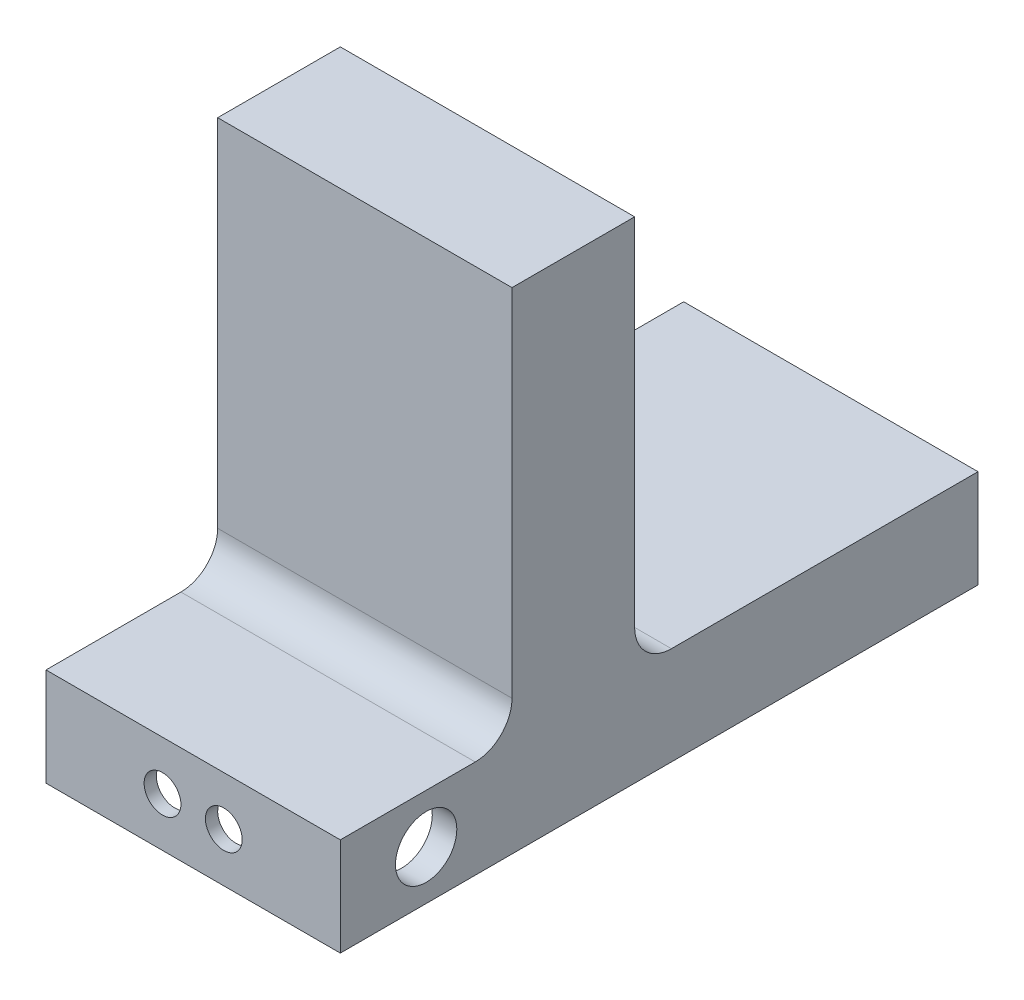
SolidWorks part; units mm, degrees
ref_plane "Plan de face" through (0, 0, 0) normal (0, 0, 1) x (1, 0, 0)
ref_plane "Plan de dessus" through (0, 0, 0) normal (0, 1, 0) x (1, 0, 0)
ref_plane "Plan de droite" through (0, 0, 0) normal (1, 0, 0) x (0, 0, -1)
sketch "Esquisse1" plane through (0, 0, 0) normal (0, 0, 1) x (1, 0, 0)
  line L0 (0, 40) -> (120, 40)
  line L1 (0, 0) -> (120, 0)
  line L2 (0, 0) -> (0, 200)
  line L3 (0, 200) -> (120, 200)
  line L4 (120, 0) -> (120, 200)
  dimension "D1" = 200
  dimension "D2" = 120
  dimension "D3" = 40
extrude "Boss.-Extru.2" add sketch "Esquisse1" along normal mid plane 50 contours L2 L1 L4 L3
sketch "Esquisse3" plane through (0, 0, 25) normal (0, 0, 1) x (1, 0, 0)
  line L0 (120, 0) -> (120, 200) construction
  line L1 (0, 0) -> (120, 0)
  line L2 (0, 0) -> (0, 40)
  line L3 (0, 40) -> (120, 40)
  line L4 (120, 0) -> (120, 40)
  dimension "D1" = 40
extrude "Boss.-Extru.3" add sketch "Esquisse3" along normal blind 70
fillet "Congé1" radius 15 1 edges at (60, 40, 25)
sketch "Esquisse4" plane through (0, 0, -25) normal (0, 0, -1) x (-1, 0, 0)
  line L0 (-120, 0) -> (-120, 200) construction
  line L1 (0, 0) -> (-120, 0)
  line L2 (0, 0) -> (0, 40)
  line L3 (0, 40) -> (-120, 40)
  line L4 (-120, 0) -> (-120, 40)
  dimension "D1" = 40
extrude "Boss.-Extru.4" add sketch "Esquisse4" along normal blind 140
fillet "Congé2" radius 15 1 edges at (60, 40, -25)
sketch "Esquisse5" plane through (0, 0, 95) normal (0, 0, 1) x (1, 0, 0)
  line L0 (0, 0) -> (120, 0) construction
  line L2 (120, 0) -> (120, 40) construction
  line L4 (35, 35) -> (85, 35)
  line L5 (35, 35) -> (35, 5)
  line L6 (35, 5) -> (85, 5)
  line L7 (85, 35) -> (85, 5)
  point P0 (60, 20)
  dimension "D1" = 20
  dimension "D2" = 60
  dimension "D3" = 25
  dimension "D4" = 50
  dimension "D5" = 30
  dimension "D6" = 15
extrude "Boss.-Extru.9" add sketch "Esquisse5" against normal blind 7.5
sketch "Esquisse7" plane through (0, 0, 0) normal (0, -1, 0) x (1, 0, 0)
  line L0 (0, 95) -> (0, -165) construction
  line L1 (10, 85) -> (110, 85)
  line L2 (10, 85) -> (10, 5)
  line L3 (10, 5) -> (110, 5)
  line L4 (110, 85) -> (110, 5)
  line L5 (0, 95) -> (120, 95) construction
  point P4 (60, 45)
  dimension "D1" = 60
  dimension "D2" = 50
  dimension "D3" = 100
  dimension "D4" = 50
  dimension "D5" = 40
  dimension "D6" = 80
extrude "Enlèv. mat.-Extru.1" cut sketch "Esquisse7" against normal blind 35
sketch "Esquisse8" plane through (0, 0, 95) normal (0, 0, 1) x (1, 0, 0)
  line L1 (120, 40) -> (0, 40) construction
  line L2 (0, 40) -> (0, 0) construction
  circle A0 centre (47.5, 20) radius 7.5
  circle A1 centre (72.5, 20) radius 7.5
  point P4 (77.7819, 21.8021)
  point P5 (45.6071, 21.8021)
  point P6 (73.2228, 21.8021)
  point P7 (0, 0)
  point P9 (40.2663, 34.8283)
  point P11 (0, 0)
  dimension "D2" = 15
  dimension "D3" = 15
  dimension "D1" = 25
  dimension "D4" = 20
  dimension "D5" = 47.5
extrude "Enlèv. mat.-Extru.7" cut sketch "Esquisse8" against normal up to next
sketch "Esquisse12" plane through (0, 0, 85) normal (0, 0, -1) x (-1, 0, 0)
  line L0 (-110, 35) -> (-110, 0) construction
  line L1 (-85, 35) -> (-35, 35)
  line L2 (-85, 35) -> (-85, 5)
  line L3 (-85, 5) -> (-35, 5)
  line L4 (-35, 35) -> (-35, 5)
  line L5 (-110, 0) -> (-10, 0) construction
  dimension "D1" = 50
  dimension "D2" = 25
  dimension "D3" = 30
  dimension "D4" = 5
extrude "Enlèv. mat.-Extru.8" cut sketch "Esquisse12" against normal blind 5
sketch "Esquisse13" plane through (120, 0, 0) normal (1, 0, 0) x (0, 0, -1)
  line L0 (-95, 0) -> (-95, 40) construction
  line L1 (-95, 40) -> (-40, 40) construction
  circle A0 centre (-60, 20) radius 12.5
  dimension "D1" = 25
  dimension "D2" = 35
  dimension "D3" = 20
extrude "Enlèv. mat.-Extru.9" cut sketch "Esquisse13" against normal through all and the other way through all
sketch "Esquisse14" plane through (0, 0, 85) normal (0, 0, -1) x (-1, 0, 0)
  line L0 (-120, 0) -> (0, 0) construction
  line L1 (-67.5, 0) -> (-52.5, 0)
  line L2 (-67.5, 0) -> (-67.5, 5)
  line L3 (-67.5, 5) -> (-52.5, 5)
  line L4 (-52.5, 0) -> (-52.5, 5)
  line L5 (-85, 5) -> (-35, 5) construction
  line L6 (-110, 35) -> (-110, 0) construction
  point P8 (-67.5, 2.5)
  dimension "D1" = 0
  dimension "D2" = 42.5
  dimension "D3" = 15
extrude "Enlèv. mat.-Extru.10" cut sketch "Esquisse14" against normal blind 3
